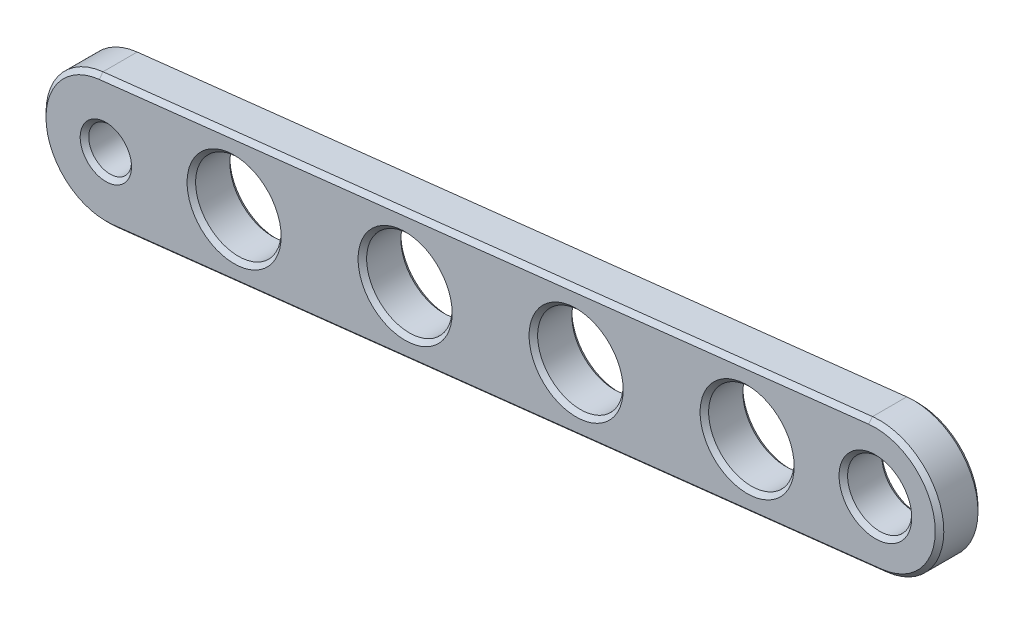
SolidWorks part; units mm, degrees
ref_plane "Front Plane" through (0, 0, 0) normal (0, 0, 1) x (1, 0, 0)
ref_plane "Top Plane" through (0, 0, 0) normal (0, 1, 0) x (1, 0, 0)
ref_plane "Right Plane" through (0, 0, 0) normal (1, 0, 0) x (0, 0, -1)
sketch "Sketch1" plane through (0, 0, 0) normal (0, 0, 1) x (1, 0, 0)
  line L0 (145.0746, 0) -> (181.0746, 4.0299) construction
  line L1 (144.7409, 2.9814) -> (180.7409, 7.0112)
  line L2 (145.4084, -2.9814) -> (181.4084, 1.0485)
  arc A0 (144.7409, 2.9814) -> (145.4084, -2.9814) centre (145.0746, 0) ccw
  arc A1 (181.4084, 1.0485) -> (180.7409, 7.0112) centre (181.0746, 4.0299) ccw
  circle A2 centre (181.0746, 4.0299) radius 1.5
  circle A3 centre (145.0746, 0) radius 1
  circle A4 centre (151.0746, 0.6716) radius 2
  circle A5 centre (175.0746, 3.3582) radius 2
  circle A6 centre (167.0746, 2.4627) radius 2
  circle A7 centre (159.0746, 1.5672) radius 2
  point P2 (163.0746, 2.0149)
  point P19 (0, 0)
  point P20 (0, 0)
  point P21 (0, 0)
  point P22 (0, 0)
  dimension "D2" = 3
  dimension "D3" = 3
  dimension "2" = 2
  dimension "D5" = 4
  dimension "D6" = 4
  dimension "D7" = 4
  dimension "D8" = 4
  dimension "D1" = 36
  dimension "D9" = 6
  dimension "D10" = 8
  dimension "D11" = 6
  dimension "D12" = 8
extrude "Boss-Extrude2" add sketch "Sketch1" along normal blind 2
chamfer "Chamfer1" distance 0.2 angle 45 20 edges at (161.0746, 1.5672, 0) (169.0746, 2.4627, 0) (177.0746, 3.3582, 0) (153.0746, 0.6716, 0) (146.0746, 0, 0) (182.5746, 4.0299, 0) (163.4084, -0.9665, 0) (184.056, 4.3636, 0) (162.7409, 4.9963, 0) (142.0932, -0.3337, 0) (161.0746, 1.5672, 2) (177.0746, 3.3582, 2) (146.0746, 0, 2) (162.7409, 4.9963, 2) (184.056, 4.3636, 2) (163.4084, -0.9665, 2) (142.0932, -0.3337, 2) (182.5746, 4.0299, 2) (153.0746, 0.6716, 2) (169.0746, 2.4627, 2)
